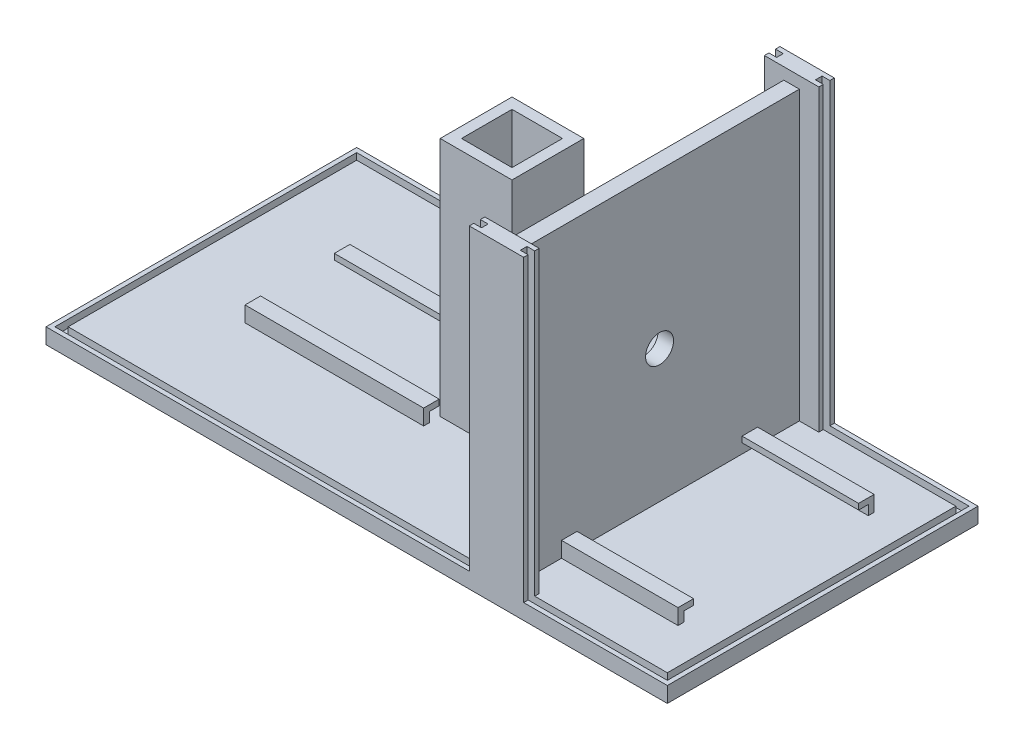
SolidWorks part; units mm, degrees
ref_plane "Ön Düzlem" through (0, 0, 0) normal (0, 0, 1) x (1, 0, 0)
ref_plane "Üst Düzlem" through (0, 0, 0) normal (0, 1, 0) x (1, 0, 0)
ref_plane "Sağ Düzlem" through (0, 0, 0) normal (1, 0, 0) x (0, 0, -1)
sketch "Çizim1" plane through (0, 0, 0) normal (0, 1, 0) x (1, 0, 0)
  line L1 (-80, -40) -> (80, -40)
  line L2 (-80, -40) -> (-80, 40)
  line L3 (-80, 40) -> (80, 40)
  line L4 (80, -40) -> (80, 40)
  line L5 (-80, -40) -> (80, 40) construction
  line L6 (-80, 40) -> (80, -40) construction
  point P0 (0, 0)
  dimension "D1" = 160
  dimension "D2" = 80
extrude "Yükseklik-Ekstrüzyon1" add sketch "Çizim1" along normal blind 4
sketch "Çizim2" plane through (0, 4, 0) normal (0, 1, 0) x (1, 0, 0)
  line L1 (-9.25, 9.25) -> (9.25, 9.25)
  line L2 (-9.25, 9.25) -> (-9.25, -9.25)
  line L3 (-9.25, -9.25) -> (9.25, -9.25)
  line L4 (9.25, 9.25) -> (9.25, -9.25)
  line L5 (-9.25, 9.25) -> (9.25, -9.25) construction
  line L6 (-9.25, -9.25) -> (9.25, 9.25) construction
  point P0 (0, 0)
  dimension "D1" = 18.5
  dimension "D2" = 18.5
extrude "Yükseklik-Ekstrüzyon2" add sketch "Çizim2" along normal blind 62
sketch "Çizim3" plane through (0, 66, 0) normal (0, 1, 0) x (1, 0, 0)
  line L1 (-6.5, 6.5) -> (6.5, 6.5)
  line L2 (-6.5, 6.5) -> (-6.5, -6.5)
  line L3 (-6.5, -6.5) -> (6.5, -6.5)
  line L4 (6.5, 6.5) -> (6.5, -6.5)
  line L5 (-6.5, 6.5) -> (6.5, -6.5) construction
  line L6 (-6.5, -6.5) -> (6.5, 6.5) construction
  point P0 (0, 0)
  dimension "D1" = 13
  dimension "D2" = 13
extrude "Kes-Ekstrüzyon1" cut sketch "Çizim3" against normal blind 33
sketch "Çizim4" plane through (9.25, 0, 0) normal (1, 0, 0) x (0, 0, -1)
  line L0 (-9.25, 4) -> (9.25, 4) construction
  line L1 (-9.25, 66) -> (-9.25, 4) construction
  circle A0 centre (0, 38.12) radius 3.6
  dimension "D1" = 34.12
  dimension "D2" = 9.25
extrude "Kes-Ekstrüzyon3" cut sketch "Çizim4" against normal blind 9.1619
sketch "Çizim6" plane through (-9.25, 0, 0) normal (-1, 0, 0) x (0, 0, 1)
  line L0 (-9.25, 66) -> (-9.25, 4) construction
  line L1 (-6.5, 33) -> (6.5, 33) construction
  circle A0 centre (0, 38.12) radius 2.5
  dimension "D1" = 9.25
  dimension "D2" = 5.12
extrude "Kes-Ekstrüzyon4" cut sketch "Çizim6" against normal blind 35
sketch "Çizim10" plane through (0, 4, 0) normal (0, 1, 0) x (1, 0, 0)
  line L0 (80, 40) -> (-80, 40) construction
  line L1 (38, -40) -> (34, -40)
  line L2 (38, -40) -> (38, 40)
  line L3 (38, 40) -> (34, 40)
  line L4 (34, -40) -> (34, 40)
  line L5 (38, -40) -> (34, 40) construction
  line L6 (38, 40) -> (34, -40) construction
  line L8 (-80, -40) -> (80, -40) construction
  line L9 (29, 40) -> (34, 40)
  line L10 (29, 40) -> (29, 36)
  line L11 (29, 36) -> (34, 36)
  line L12 (34, 40) -> (34, 36)
  line L13 (29, 40) -> (34, 36) construction
  line L14 (29, 36) -> (34, 40) construction
  line L15 (29, -36) -> (34, -36)
  line L16 (29, -36) -> (29, -40)
  line L17 (29, -40) -> (34, -40)
  line L18 (34, -36) -> (34, -40)
  line L19 (29, -36) -> (34, -40) construction
  line L20 (29, -40) -> (34, -36) construction
  point P0 (36, 0)
  point P9 (31.5, 38)
  point P14 (31.5, -38)
  line M18 (80, 40) -> (-80, 40)
  line M20 (-80, -40) -> (80, -40)
  dimension "D1" = 4
  dimension "D3" = 4
  dimension "D4" = 5
  dimension "D5" = 0
  dimension "D6" = 0
  dimension "D7" = 5
  dimension "D8" = 4
  dimension "D9" = 0
  dimension "D10" = 0
extrude "Yükseklik-Ekstrüzyon5" add sketch "Çizim10" along normal blind 77 contours L4 L2 M20 M18 | L10 L11 L4 M18 | L15 L16 L4 M20
sketch "Çizim11" plane through (38, 0, 0) normal (1, 0, 0) x (0, 0, -1)
  line L0 (-40, 81) -> (-40, 4) construction
  line L1 (-40, 4) -> (40, 4) construction
  circle A0 centre (0, 38.12) radius 3.6
  dimension "D1" = 40
  dimension "D2" = 34.12
extrude "Kes-Ekstrüzyon6" cut sketch "Çizim11" against normal blind 5
sketch "Çizim12" plane through (0, 81, 0) normal (0, 1, 0) x (1, 0, 0)
  line L0 (29, -36) -> (34, -36) construction
  line L1 (29, -37.15) -> (31, -37.15)
  line L2 (29, -37.15) -> (29, -38.85)
  line L3 (29, -38.85) -> (31, -38.85)
  line L4 (31, -37.15) -> (31, -38.85)
  line L5 (29, -37.15) -> (31, -38.85) construction
  line L6 (29, -38.85) -> (31, -37.15) construction
  line L7 (29, -36) -> (29, -40) construction
  line L10 (29, 36) -> (34, 36) construction
  line L11 (29, 38.85) -> (31, 38.85)
  line L12 (29, 38.85) -> (29, 37.15)
  line L13 (29, 37.15) -> (31, 37.15)
  line L14 (31, 38.85) -> (31, 37.15)
  line L15 (29, 38.85) -> (31, 37.15) construction
  line L16 (29, 37.15) -> (31, 38.85) construction
  line L17 (29, 40) -> (29, 36) construction
  point P0 (30, -38)
  point P11 (30, 38)
  dimension "D1" = 2
  dimension "D2" = 1.7
  dimension "D3" = 2
  dimension "D4" = 0
  dimension "D5" = 2
  dimension "D6" = 1.7
  dimension "D7" = 2
  dimension "D8" = 0
extrude "Kes-Ekstrüzyon7" cut sketch "Çizim12" against normal blind 79
sketch "Çizim13" plane through (0, 4, 0) normal (0, 1, 0) x (1, 0, 0)
  line L1 (-78.85, 38.85) -> (29, 38.85)
  line L2 (-78.85, 38.85) -> (-78.85, 37.15)
  line L3 (-78.85, 37.15) -> (29, 37.15)
  line L4 (29, 38.85) -> (29, 37.15)
  line L5 (-78.85, 38.85) -> (29, 37.15) construction
  line L6 (-78.85, 37.15) -> (29, 38.85) construction
  line L7 (-80, 40) -> (-80, -40) construction
  line L8 (29, 40) -> (-80, 40) construction
  line L9 (-80, -40) -> (29, -40) construction
  line L10 (-78.85, 38.85) -> (-77.15, 38.85)
  line L11 (-78.85, 38.85) -> (-78.85, -38.85)
  line L12 (-78.85, -38.85) -> (-77.15, -38.85)
  line L13 (-77.15, 38.85) -> (-77.15, -38.85)
  line L14 (-78.85, 38.85) -> (-77.15, -38.85) construction
  line L15 (-78.85, -38.85) -> (-77.15, 38.85) construction
  line L17 (-78.85, -37.15) -> (29, -37.15)
  line L18 (-78.85, -37.15) -> (-78.85, -38.85)
  line L19 (-78.85, -38.85) -> (29, -38.85)
  line L20 (29, -37.15) -> (29, -38.85)
  line L21 (-78.85, -37.15) -> (29, -38.85) construction
  line L22 (-78.85, -38.85) -> (29, -37.15) construction
  point P0 (-24.925, 38)
  point P10 (-78, 0)
  point P17 (-24.925, -38)
  line M22 (29, -38.85) -> (29, -37.15)
  line M28 (29, 37.15) -> (29, 38.85)
  dimension "D1" = 107.85
  dimension "D2" = 1.7
  dimension "D3" = 1.15
  dimension "D4" = 1.15
  dimension "D5" = 77.7
  dimension "D6" = 1.7
  dimension "D7" = 1.15
  dimension "D8" = 1.15
  dimension "D9" = 107.85
  dimension "D10" = 1.7
  dimension "D11" = 1.15
  dimension "D12" = 1.15
extrude "Kes-Ekstrüzyon8" cut sketch "Çizim13" against normal blind 2 contours L13 L19 L17 M22 | L11 L17 L13 L3 | L17 L11 L12 L13 | L1 L13 L3 M28 | L13 L1 L2 L3
sketch "Çizim14" plane through (0, 4, 0) normal (0, 1, 0) x (1, 0, 0)
  line L0 (-9.25, 9.25) -> (-9.25, -9.25) construction
  line L1 (-55.25, -9.5) -> (-9.25, -9.5)
  line L2 (-55.25, -9.5) -> (-55.25, -13.5)
  line L3 (-55.25, -13.5) -> (-9.25, -13.5)
  line L4 (-9.25, -9.5) -> (-9.25, -13.5)
  line L5 (-55.25, -9.5) -> (-9.25, -13.5) construction
  line L6 (-55.25, -13.5) -> (-9.25, -9.5) construction
  line L7 (-9.25, -9.25) -> (9.25, -9.25) construction
  line L8 (-55.25, 13.5) -> (-9.25, 13.5)
  line L9 (-55.25, 13.5) -> (-55.25, 9.5)
  line L10 (-55.25, 9.5) -> (-9.25, 9.5)
  line L11 (-9.25, 13.5) -> (-9.25, 9.5)
  line L12 (-55.25, 13.5) -> (-9.25, 9.5) construction
  line L13 (-55.25, 9.5) -> (-9.25, 13.5) construction
  line L14 (-9.25, 9.25) -> (-9.25, -9.25) construction
  line L15 (9.25, 9.25) -> (-9.25, 9.25) construction
  point P0 (-32.25, -11.5)
  point P9 (-32.25, 11.5)
  dimension "D1" = 46
  dimension "D2" = 4
  dimension "D3" = 0
  dimension "D4" = 0.25
  dimension "D5" = 46
  dimension "D6" = 4
  dimension "D7" = 0
  dimension "D8" = 0.25
extrude "Yükseklik-Ekstrüzyon13" add sketch "Çizim14" along normal blind 4 separate body
sketch "Çizim15" plane through (-55.25, 0, 0) normal (-1, 0, 0) x (0, 0, 1)
  line L0 (-13.5, 8) -> (-9.5, 8) construction
  line L1 (-12, 6.5) -> (-9.5, 6.5)
  line L2 (-12, 6.5) -> (-12, 4)
  line L3 (-12, 4) -> (-9.5, 4)
  line L4 (-9.5, 6.5) -> (-9.5, 4)
  line L5 (-12, 6.5) -> (-9.5, 4) construction
  line L6 (-12, 4) -> (-9.5, 6.5) construction
  line L7 (-13.5, 8) -> (-13.5, 4) construction
  line L8 (9.5, 8) -> (13.5, 8) construction
  line L9 (9.5, 6.5) -> (12, 6.5)
  line L10 (9.5, 6.5) -> (9.5, 4)
  line L11 (9.5, 4) -> (12, 4)
  line L12 (12, 6.5) -> (12, 4)
  line L13 (9.5, 6.5) -> (12, 4) construction
  line L14 (9.5, 4) -> (12, 6.5) construction
  line L15 (9.5, 8) -> (9.5, 4) construction
  point P0 (-10.75, 5.25)
  point P9 (10.75, 5.25)
  dimension "D1" = 2.5
  dimension "D2" = 2.5
  dimension "D3" = 1.5
  dimension "D4" = 1.5
  dimension "D5" = 2.5
  dimension "D6" = 2.5
  dimension "D7" = 1.5
  dimension "D8" = 0
extrude "Kes-Ekstrüzyon9" cut sketch "Çizim15" against normal blind 46
sketch "Çizim16" plane through (0, 4, 0) normal (0, 1, 0) x (1, 0, 0)
  line L0 (38, 25.25) -> (68, 25.25)
  line L1 (38, -21.25) -> (68, -21.25)
  line L2 (38, -21.25) -> (38, -25.25)
  line L3 (38, -25.25) -> (68, -25.25)
  line L4 (68, -21.25) -> (68, -25.25)
  line L5 (38, -21.25) -> (68, -25.25) construction
  line L6 (38, -25.25) -> (68, -21.25) construction
  line L7 (38, 25.25) -> (38, 21.25)
  line L8 (38, 21.25) -> (68, 21.25)
  line L9 (68, 25.25) -> (68, 21.25)
  line L10 (38, 25.25) -> (68, 21.25) construction
  line L11 (38, 21.25) -> (68, 25.25) construction
  line L12 (38, -40) -> (38, 40) construction
  line L13 (38, -40) -> (80, -40) construction
  point P0 (53, -23.25)
  point P5 (53, 23.25)
  point P10 (38, -23.25)
  dimension "D1" = 30
  dimension "D2" = 4
  dimension "D3" = 30
  dimension "D4" = 4
  dimension "D5" = 42.5
  dimension "D6" = 0
  dimension "D7" = 14.75
  dimension "D8" = 0
extrude "Yükseklik-Ekstrüzyon14" add sketch "Çizim16" along normal blind 4
sketch "Çizim17" plane through (68, 0, 0) normal (1, 0, 0) x (0, 0, -1)
  line L1 (-21.25, 4) -> (-23.75, 4)
  line L2 (-21.25, 4) -> (-21.25, 6.5)
  line L3 (-21.25, 6.5) -> (-23.75, 6.5)
  line L4 (-23.75, 4) -> (-23.75, 6.5)
  line L6 (21.25, 4) -> (23.75, 4)
  line L7 (21.25, 4) -> (21.25, 6.5)
  line L8 (21.25, 6.5) -> (23.75, 6.5)
  line L9 (23.75, 4) -> (23.75, 6.5)
  dimension "D1" = 2.5
  dimension "D2" = 2.5
  dimension "D3" = 2.5
  dimension "D4" = 2.5
extrude "Kes-Ekstrüzyon10" cut sketch "Çizim17" against normal blind 30
sketch "Çizim18" plane through (0, 4, 0) normal (0, 1, 0) x (1, 0, 0)
  line L0 (38, 36) -> (43, 36)
  line L1 (38, -40) -> (43, -40)
  line L2 (38, -40) -> (38, -36)
  line L3 (38, -36) -> (43, -36)
  line L4 (43, -40) -> (43, -36)
  line L5 (38, 36) -> (38, 40)
  line L6 (38, 40) -> (43, 40)
  line L7 (43, 36) -> (43, 40)
  line L8 (80, 40) -> (38, 40) construction
  line L9 (38, -40) -> (38, -25.25) construction
  dimension "D1" = 5
  dimension "D2" = 4
  dimension "D3" = 5
  dimension "D4" = 4
  dimension "D5" = 0
  dimension "D6" = 0
extrude "Yükseklik-Ekstrüzyon15" add sketch "Çizim18" along normal blind 77
sketch "Çizim20" plane through (0, 81, 0) normal (0, 1, 0) x (1, 0, 0)
  line L0 (43, -36) -> (38, -36) construction
  line L1 (41, -37.15) -> (43, -37.15)
  line L2 (41, -37.15) -> (41, -38.85)
  line L3 (41, -38.85) -> (43, -38.85)
  line L4 (43, -37.15) -> (43, -38.85)
  line L5 (41, -37.15) -> (43, -38.85) construction
  line L6 (41, -38.85) -> (43, -37.15) construction
  line L7 (43, -40) -> (43, -36) construction
  line L8 (43, 36) -> (43, 40) construction
  line L9 (41, 38.85) -> (43, 38.85)
  line L10 (41, 38.85) -> (41, 37.15)
  line L11 (41, 37.15) -> (43, 37.15)
  line L12 (43, 38.85) -> (43, 37.15)
  line L13 (41, 38.85) -> (43, 37.15) construction
  line L14 (41, 37.15) -> (43, 38.85) construction
  line L15 (43, 40) -> (29, 40) construction
  point P0 (42, -38)
  point P9 (42, 38)
  dimension "D1" = 2
  dimension "D2" = 1.7
  dimension "D3" = 1.15
  dimension "D4" = 0
  dimension "D5" = 2
  dimension "D6" = 1.7
  dimension "D7" = 0
  dimension "D8" = 1.15
extrude "Kes-Ekstrüzyon11" cut sketch "Çizim20" against normal blind 79
sketch "Çizim21" plane through (0, 4, 0) normal (0, 1, 0) x (1, 0, 0)
  line L0 (43, -40) -> (80, -40) construction
  line L1 (43, -37.15) -> (78.85, -37.15)
  line L2 (43, -37.15) -> (43, -38.85)
  line L3 (43, -38.85) -> (78.85, -38.85)
  line L4 (78.85, -37.15) -> (78.85, -38.85)
  line L5 (43, -37.15) -> (78.85, -38.85) construction
  line L6 (43, -38.85) -> (78.85, -37.15) construction
  line L7 (80, -40) -> (80, 40) construction
  line L8 (80, 40) -> (43, 40) construction
  line L9 (77.15, 38.85) -> (78.85, 38.85)
  line L10 (77.15, 38.85) -> (77.15, -38.85)
  line L11 (77.15, -38.85) -> (78.85, -38.85)
  line L12 (78.85, 38.85) -> (78.85, -38.85)
  line L13 (77.15, 38.85) -> (78.85, -38.85) construction
  line L14 (77.15, -38.85) -> (78.85, 38.85) construction
  line L15 (42.8032, 38.85) -> (78.85, 38.85)
  line L16 (42.8032, 38.85) -> (42.8032, 37.15)
  line L17 (42.8032, 37.15) -> (78.85, 37.15)
  line L18 (78.85, 38.85) -> (78.85, 37.15)
  point P0 (60.925, -38)
  point P9 (78, 0)
  line M22 (43, -37.15) -> (43, -38.85)
  line M28 (43, 38.85) -> (43, 37.15)
  dimension "D1" = 35.85
  dimension "D2" = 1.7
  dimension "D3" = 1.15
  dimension "D4" = 1.15
  dimension "D5" = 77.7
  dimension "D6" = 1.7
  dimension "D7" = 1.15
  dimension "D8" = 1.15
  dimension "D9" = 1.15
  dimension "D10" = 1.15
extrude "Kes-Ekstrüzyon12" cut sketch "Çizim21" against normal blind 2 contours L10 L1 L3 M22 | L1 L10 L3 L4 | L17 L10 L1 L12 | L17 L10 L15 M28 | L10 L17 L12 L9
sketch "Çizim22" plane through (0, 81, 0) normal (0, 1, 0) x (1, 0, 0)
  line L1 (34, 36) -> (38, 36)
  line L2 (34, 36) -> (34, -36)
  line L3 (34, -36) -> (38, -36)
  line L4 (38, 36) -> (38, -36)
  line L5 (34, 36) -> (38, -36) construction
  line L6 (34, -36) -> (38, 36) construction
  point P0 (36, 0)
  dimension "D1" = 4
  dimension "D2" = 2
extrude "Kes-Ekstrüzyon13" cut sketch "Çizim22" against normal blind 3
equation "\"2.5.00mm\"=6"
